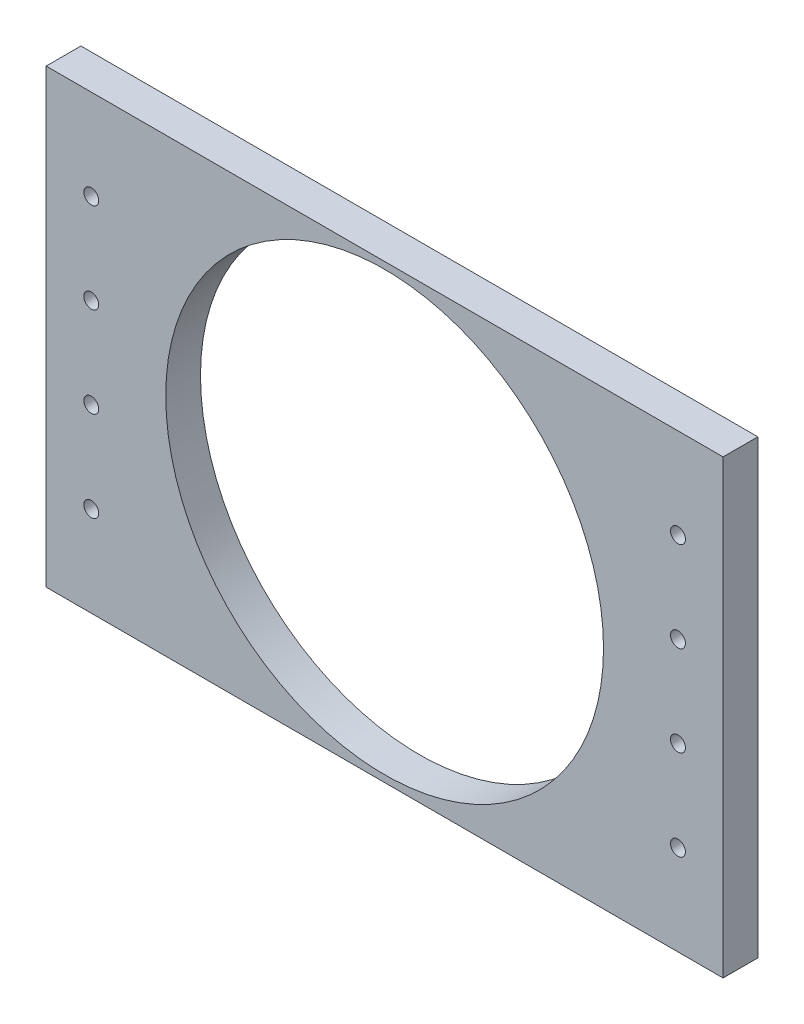
SolidWorks part; units mm, degrees
ref_plane "前视基准面" through (0, 0, 0) normal (0, 0, 1) x (1, 0, 0)
ref_plane "上视基准面" through (0, 0, 0) normal (0, 1, 0) x (1, 0, 0)
ref_plane "右视基准面" through (0, 0, 0) normal (1, 0, 0) x (0, 0, -1)
other "Configuration Table"
sketch "草图1" plane through (0, 0, 0) normal (0, 0, 1) x (1, 0, 0)
  line L0 (0, 0) -> (0, 50) construction
  line L1 (-75, 50) -> (75, 50)
  line L2 (-75, 50) -> (-75, -50)
  line L3 (-75, -50) -> (75, -50)
  line L4 (75, 50) -> (75, -50)
  line L5 (-75, 50) -> (75, -50) construction
  line L6 (-75, -50) -> (75, 50) construction
  line L7 (-65, 50) -> (-65, -50) construction
  circle A0 centre (-65, 30) radius 1.65
  circle A1 centre (-65, 10) radius 1.65
  circle A2 centre (-65, -10) radius 1.65
  circle A3 centre (-65, -30) radius 1.65
  circle A4 centre (65, -30) radius 1.65
  circle A5 centre (65, -10) radius 1.65
  circle A6 centre (65, 10) radius 1.65
  circle A7 centre (65, 30) radius 1.65
  circle A8 centre (0, 0) radius 48.5
  point P0 (0, 0)
  dimension "D4" = 3.3
  dimension "D6" = 3.3
  dimension "D7" = 3.3
  dimension "D8" = 3.3
  dimension "D12" = 97
  dimension "D1" = 150
  dimension "D2" = 100
  dimension "D3" = 10
  dimension "D5" = 20
  dimension "D9" = 20
  dimension "D10" = 20
  dimension "D11" = 20
extrude "凸台-拉伸1" add sketch "草图1" along normal blind 7.7
